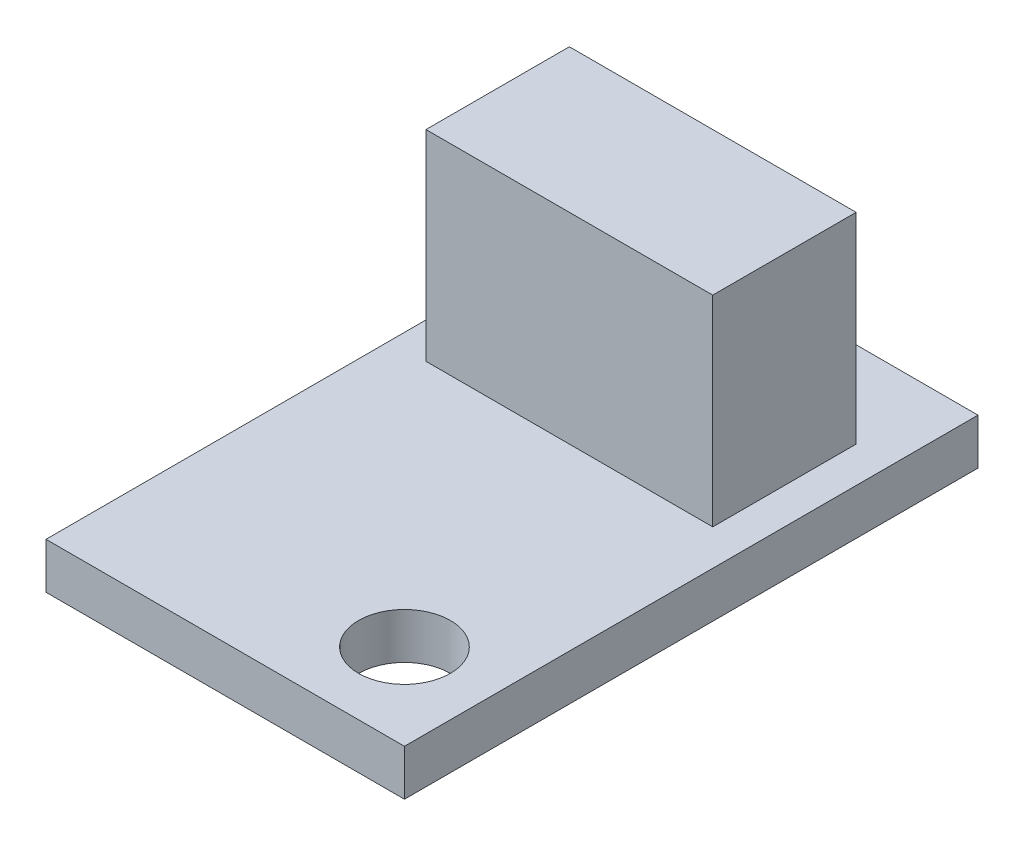
SolidWorks part; units mm, degrees
ref_plane "Front Plane" through (0, 0, 0) normal (0, 0, 1) x (1, 0, 0)
ref_plane "Top Plane" through (0, 0, 0) normal (0, 1, 0) x (1, 0, 0)
ref_plane "Right Plane" through (0, 0, 0) normal (1, 0, 0) x (0, 0, -1)
sketch "Sketch1" plane through (0, 0, 0) normal (0, 1, 0) x (1, 0, 0)
  line L1 (-6.25, 0) -> (6.25, 0)
  line L2 (-6.25, 0) -> (-6.25, 20)
  line L3 (-6.25, 20) -> (6.25, 20)
  line L4 (6.25, 0) -> (6.25, 20)
  circle A0 centre (3.25, 3) radius 1.6
  dimension "D3" = 3.2
  dimension "D1" = 12.5
  dimension "D2" = 20
  dimension "D4" = 3
  dimension "D5" = 3
extrude "Boss-Extrude1" add sketch "Sketch1" along normal blind 1.6
sketch "Sketch2" plane through (0, 1.6, 0) normal (0, 1, 0) x (1, 0, 0)
  line L0 (0, 0) -> (0, 50000) construction
  line L1 (-5, 17) -> (5, 17)
  line L2 (-5, 17) -> (-5, 12)
  line L3 (-5, 12) -> (5, 12)
  line L4 (5, 17) -> (5, 12)
  line L5 (-6.25, 0) -> (6.25, 0) construction
  line L6 (6.25, 20) -> (-6.25, 20) construction
  point P8 (0, 0)
  dimension "D1" = 10
  dimension "D2" = 5
  dimension "D3" = 3
extrude "Boss-Extrude2" add sketch "Sketch2" along normal blind 7
